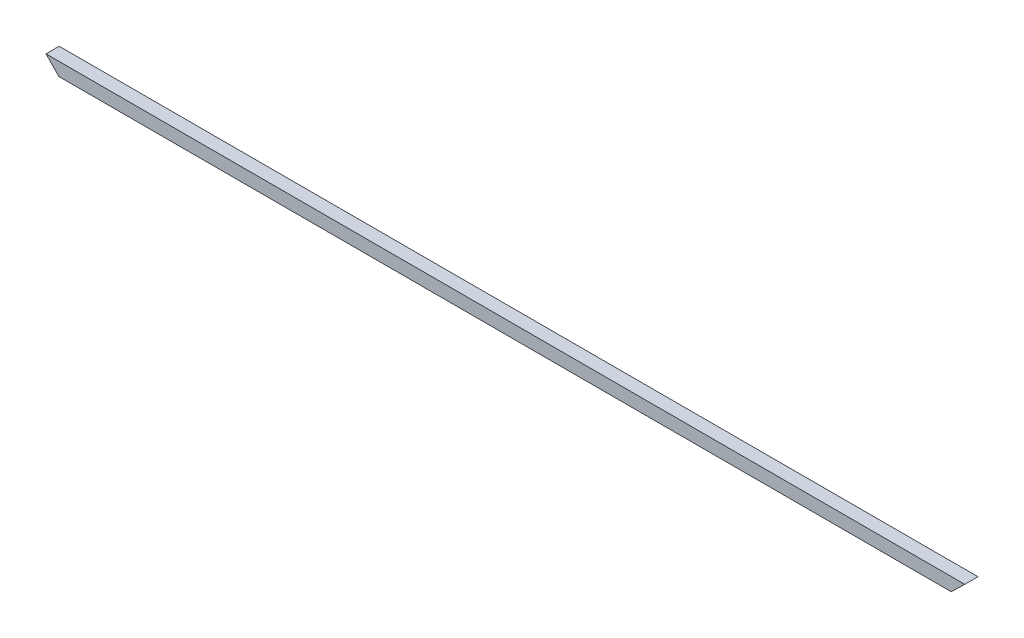
SolidWorks part; units mm, degrees
ref_plane "Front Plane" through (0, 0, 0) normal (0, 0, 1) x (1, 0, 0)
ref_plane "Top Plane" through (0, 0, 0) normal (0, 1, 0) x (1, 0, 0)
ref_plane "Right Plane" through (0, 0, 0) normal (1, 0, 0) x (0, 0, -1)
sketch "Sketch2" plane through (0, 0, 0) normal (0, 0, 1) x (1, 0, 0)
  line L0 (-2761.9389, 0) -> (24.3611, 0)
  line L1 (55, 0) -> (-55, 0) construction
  line L2 (24.3611, 0) -> (-16.7718, -40)
  line L3 (-16.7718, -40) -> (-2723.0406, -40)
  line L4 (-2723.0406, -40) -> (-2761.9389, 0)
  dimension "D1" = 45.8
  dimension "D2" = 44.2
  dimension "D3" = 2786.3
  dimension "D4" = 40
extrude "Boss-Extrude1" add sketch "Sketch2" along normal blind 40
